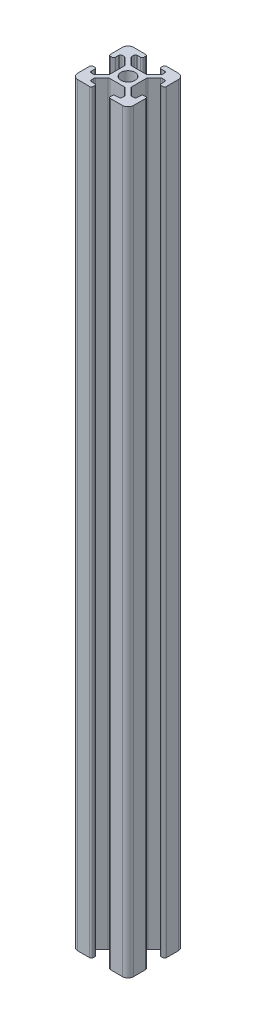
SolidWorks part; units mm, degrees
ref_plane "前视基准面" through (0, 0, 0) normal (0, 0, 1) x (1, 0, 0)
ref_plane "上视基准面" through (0, 0, 0) normal (0, 1, 0) x (1, 0, 0)
ref_plane "右视基准面" through (0, 0, 0) normal (1, 0, 0) x (0, 0, -1)
sketch "草图1" plane through (0, 0, 0) normal (0, 1, 0) x (1, 0, 0)
  line L0 (3.1, 8.8) -> (3.1, 9.4)
  line L1 (-10, -10) -> (10, -10) construction
  line L2 (-10, -10) -> (-10, 10) construction
  line L3 (-10, 10) -> (10, 10) construction
  line L4 (10, -10) -> (10, 10) construction
  line L5 (-10, -10) -> (10, 10) construction
  line L6 (-10, 10) -> (10, -10) construction
  line L7 (3.7, 10) -> (8, 10)
  line L8 (0, 10) -> (0, -10) construction
  line L9 (3.7, 8.2) -> (4.9, 8.2)
  line L10 (5.3243, 6.3849) -> (3.0151, 4.0757)
  line L11 (2.5908, 3.9) -> (0, 3.9)
  line L12 (5.5, 7.6) -> (5.5, 6.8092)
  line L13 (10, 3.7) -> (10, 8)
  line L14 (8.8, 3.1) -> (9.4, 3.1)
  line L15 (8.2, 3.7) -> (8.2, 4.9)
  line L16 (7.6, 5.5) -> (6.8092, 5.5)
  line L17 (6.3849, 5.3243) -> (4.0757, 3.0151)
  line L18 (3.9, 2.5908) -> (3.9, 0)
  line L19 (3.9, -2.5908) -> (3.9, 0)
  line L20 (2.5908, -3.9) -> (0, -3.9)
  line L21 (5.3243, -6.3849) -> (3.0151, -4.0757)
  line L22 (6.3849, -5.3243) -> (4.0757, -3.0151)
  line L23 (5.5, -7.6) -> (5.5, -6.8092)
  line L24 (3.7, -8.2) -> (4.9, -8.2)
  line L25 (3.1, -8.8) -> (3.1, -9.4)
  line L26 (3.7, -10) -> (8, -10)
  line L27 (10, -3.7) -> (10, -8)
  line L28 (8.8, -3.1) -> (9.4, -3.1)
  line L29 (8.2, -3.7) -> (8.2, -4.9)
  line L30 (7.6, -5.5) -> (6.8092, -5.5)
  line L31 (-2.5908, -3.9) -> (0, -3.9)
  line L32 (-3.9, -2.5908) -> (-3.9, 0)
  line L33 (-6.3849, -5.3243) -> (-4.0757, -3.0151)
  line L34 (-5.3243, -6.3849) -> (-3.0151, -4.0757)
  line L35 (-7.6, -5.5) -> (-6.8092, -5.5)
  line L36 (-8.2, -3.7) -> (-8.2, -4.9)
  line L37 (-8.8, -3.1) -> (-9.4, -3.1)
  line L38 (-10, -3.7) -> (-10, -8)
  line L39 (-3.7, -10) -> (-8, -10)
  line L40 (-3.1, -8.8) -> (-3.1, -9.4)
  line L41 (-3.7, -8.2) -> (-4.9, -8.2)
  line L42 (-5.5, -7.6) -> (-5.5, -6.8092)
  line L43 (-3.9, 2.5908) -> (-3.9, 0)
  line L44 (-2.5908, 3.9) -> (0, 3.9)
  line L45 (-5.3243, 6.3849) -> (-3.0151, 4.0757)
  line L46 (-6.3849, 5.3243) -> (-4.0757, 3.0151)
  line L47 (-5.5, 7.6) -> (-5.5, 6.8092)
  line L48 (-3.7, 8.2) -> (-4.9, 8.2)
  line L49 (-3.1, 8.8) -> (-3.1, 9.4)
  line L50 (-3.7, 10) -> (-8, 10)
  line L51 (-10, 3.7) -> (-10, 8)
  line L52 (-8.8, 3.1) -> (-9.4, 3.1)
  line L53 (-8.2, 3.7) -> (-8.2, 4.9)
  line L54 (-7.6, 5.5) -> (-6.8092, 5.5)
  circle A0 centre (0, 0) radius 2.5
  arc A1 (3.0151, 4.0757) -> (2.5908, 3.9) centre (2.5908, 4.5) cw
  arc A2 (5.5, 6.8092) -> (5.3243, 6.3849) centre (4.9, 6.8092) cw
  arc A3 (5.5, 7.6) -> (4.9, 8.2) centre (4.9, 7.6) ccw
  arc A4 (3.1, 8.8) -> (3.7, 8.2) centre (3.7, 8.8) ccw
  arc A5 (3.7, 10) -> (3.1, 9.4) centre (3.7, 9.4) ccw
  arc A6 (10, 3.7) -> (9.4, 3.1) centre (9.4, 3.7) cw
  arc A7 (8.8, 3.1) -> (8.2, 3.7) centre (8.8, 3.7) cw
  arc A8 (7.6, 5.5) -> (8.2, 4.9) centre (7.6, 4.9) cw
  arc A9 (6.8092, 5.5) -> (6.3849, 5.3243) centre (6.8092, 4.9) ccw
  arc A10 (4.0757, 3.0151) -> (3.9, 2.5908) centre (4.5, 2.5908) ccw
  arc A11 (10, 8) -> (8, 10) centre (8, 8) ccw
  arc A12 (3.0151, -4.0757) -> (2.5908, -3.9) centre (2.5908, -4.5) ccw
  arc A13 (4.0757, -3.0151) -> (3.9, -2.5908) centre (4.5, -2.5908) cw
  arc A14 (5.5, -6.8092) -> (5.3243, -6.3849) centre (4.9, -6.8092) ccw
  arc A15 (6.8092, -5.5) -> (6.3849, -5.3243) centre (6.8092, -4.9) cw
  arc A16 (5.5, -7.6) -> (4.9, -8.2) centre (4.9, -7.6) cw
  arc A17 (3.1, -8.8) -> (3.7, -8.2) centre (3.7, -8.8) cw
  arc A18 (3.7, -10) -> (3.1, -9.4) centre (3.7, -9.4) cw
  arc A19 (8, -10) -> (10, -8) centre (8, -8) ccw
  arc A20 (10, -3.7) -> (9.4, -3.1) centre (9.4, -3.7) ccw
  arc A21 (8.8, -3.1) -> (8.2, -3.7) centre (8.8, -3.7) ccw
  arc A22 (7.6, -5.5) -> (8.2, -4.9) centre (7.6, -4.9) ccw
  arc A23 (-4.0757, -3.0151) -> (-3.9, -2.5908) centre (-4.5, -2.5908) ccw
  arc A24 (-3.0151, -4.0757) -> (-2.5908, -3.9) centre (-2.5908, -4.5) cw
  arc A25 (-6.8092, -5.5) -> (-6.3849, -5.3243) centre (-6.8092, -4.9) ccw
  arc A26 (-5.5, -6.8092) -> (-5.3243, -6.3849) centre (-4.9, -6.8092) cw
  arc A27 (-7.6, -5.5) -> (-8.2, -4.9) centre (-7.6, -4.9) cw
  arc A28 (-8.8, -3.1) -> (-8.2, -3.7) centre (-8.8, -3.7) cw
  arc A29 (-10, -3.7) -> (-9.4, -3.1) centre (-9.4, -3.7) cw
  arc A30 (-10, -8) -> (-8, -10) centre (-8, -8) ccw
  arc A31 (-3.7, -10) -> (-3.1, -9.4) centre (-3.7, -9.4) ccw
  arc A32 (-3.1, -8.8) -> (-3.7, -8.2) centre (-3.7, -8.8) ccw
  arc A33 (-5.5, -7.6) -> (-4.9, -8.2) centre (-4.9, -7.6) ccw
  arc A34 (-3.0151, 4.0757) -> (-2.5908, 3.9) centre (-2.5908, 4.5) ccw
  arc A35 (-4.0757, 3.0151) -> (-3.9, 2.5908) centre (-4.5, 2.5908) cw
  arc A36 (-5.5, 6.8092) -> (-5.3243, 6.3849) centre (-4.9, 6.8092) ccw
  arc A37 (-6.8092, 5.5) -> (-6.3849, 5.3243) centre (-6.8092, 4.9) cw
  arc A38 (-5.5, 7.6) -> (-4.9, 8.2) centre (-4.9, 7.6) cw
  arc A39 (-3.1, 8.8) -> (-3.7, 8.2) centre (-3.7, 8.8) cw
  arc A40 (-3.7, 10) -> (-3.1, 9.4) centre (-3.7, 9.4) cw
  arc A41 (-8, 10) -> (-10, 8) centre (-8, 8) ccw
  arc A42 (-10, 3.7) -> (-9.4, 3.1) centre (-9.4, 3.7) ccw
  arc A43 (-8.8, 3.1) -> (-8.2, 3.7) centre (-8.8, 3.7) ccw
  arc A44 (-7.6, 5.5) -> (-8.2, 4.9) centre (-7.6, 4.9) ccw
  point P0 (0, 0)
  point P20 (5.5, 6.5607)
  point P25 (3.1, 8.2)
  point P28 (3.1, 10)
  point P156 (0, 0)
  dimension "D3" = 5
  dimension "D9" = 0.6
  dimension "D10" = 2
  dimension "D1" = 20
  dimension "D2" = 20
  dimension "D4" = 6.1
  dimension "D5" = 1.5
  dimension "D6" = 1.8
  dimension "D7" = 3.1
  dimension "D8" = 4.5
  dimension "D11" = 4
extrude "凸台-拉伸1" add sketch "草图1" along normal blind 270
